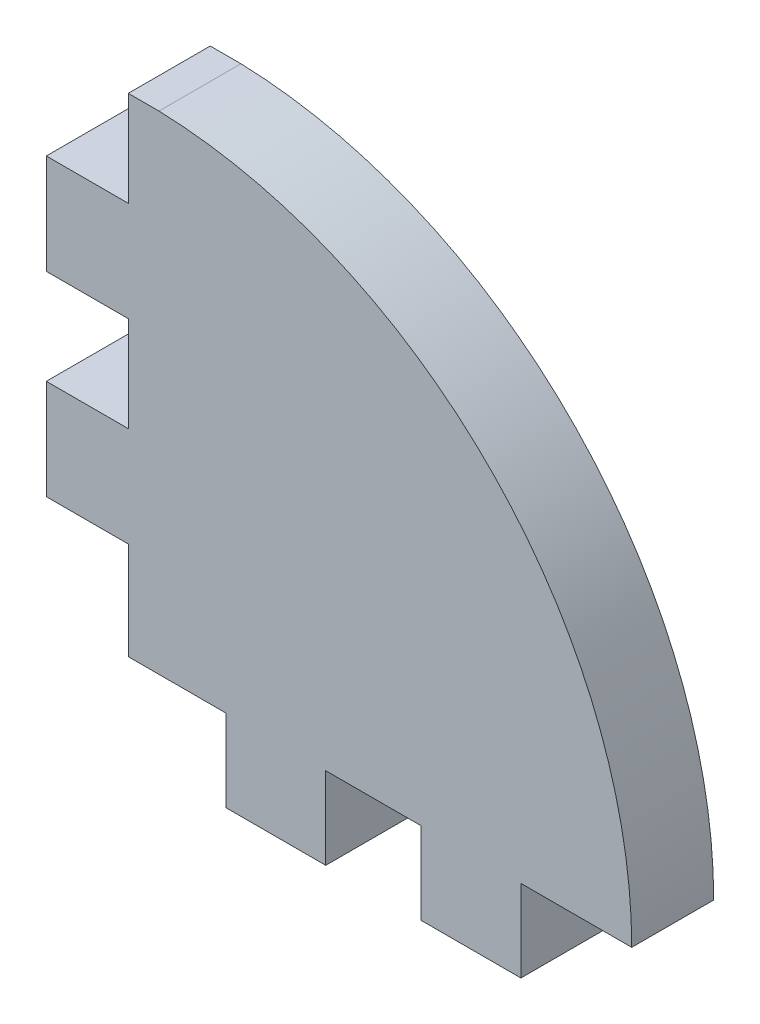
SolidWorks part; units mm, degrees
material "Oak"
ref_plane "Front Plane" through (0, 0, 0) normal (0, 0, 1) x (1, 0, 0)
ref_plane "Top Plane" through (0, 0, 0) normal (0, 1, 0) x (1, 0, 0)
ref_plane "Right Plane" through (0, 0, 0) normal (1, 0, 0) x (0, 0, -1)
sketch "Sketch1" plane through (0, 0, 0) normal (0, 0, 1) x (1, 0, 0)
  line L0 (5.334, 31.75) -> (0, 31.75) construction
  line L2 (0, -5.334) -> (38.1, -5.334)
  line L3 (0, -5.334) -> (0, 31.75)
  line L4 (0, 31.75) -> (38.1, 31.75)
  line L6 (38.1, -5.334) -> (38.1, 31.75)
  arc A0 (5.334, 31.75) -> (38.1, 0) centre (6.3342, 0) cw
extrude "Boss-Extrude1" add sketch "Sketch1" against normal blind 5.334 contours A0 L4 L3 L2 L6
sketch "Sketch2" plane through (0, 0, 0) normal (0, 0, 1) x (1, 0, 0)
  line L0 (0, -5.334) -> (38.1, -5.334) construction
  line L1 (11.684, -5.334) -> (5.4864, -5.334)
  line L2 (11.684, -5.334) -> (11.684, 0)
  line L3 (0, 31.75) -> (5.334, 31.75)
  line L4 (0, 31.75) -> (0, 25.5524)
  line L5 (0, 25.5524) -> (5.334, 25.5524)
  line L6 (5.334, 31.75) -> (5.334, 25.5524)
  line L7 (11.684, 0) -> (5.4864, 0)
  line L8 (5.4864, -5.334) -> (5.4864, 0)
  line L9 (0, 0.1524) -> (0, -5.334)
  line L10 (0, -5.334) -> (5.4864, -5.334)
  line L11 (5.334, 0.1524) -> (5.334, 0)
  line L12 (5.334, 0) -> (5.4864, 0)
  line L13 (0, 19.05) -> (0, 12.8524)
  line L14 (0, 19.05) -> (5.334, 19.05)
  line L15 (5.334, 19.05) -> (5.334, 12.8524)
  line L16 (24.384, 0) -> (18.1864, 0)
  line L17 (0, 12.8524) -> (5.334, 12.8524)
  line L18 (24.384, -5.334) -> (24.384, 0)
  line L19 (24.384, -5.334) -> (18.1864, -5.334)
  line L20 (18.1864, -5.334) -> (18.1864, 0)
  line L21 (37.084, 0) -> (30.8864, 0)
  line L22 (0, 6.35) -> (0, 0.1524)
  line L23 (0, 6.35) -> (5.334, 6.35)
  line L24 (5.334, 6.35) -> (5.334, 0.1524)
  line L25 (0, 0.1524) -> (5.334, 0.1524)
  line L26 (0, -5.334) -> (0, 31.75) construction
  line L27 (37.084, -5.334) -> (37.084, 0)
  line L28 (37.084, -5.334) -> (30.8864, -5.334)
  line L29 (30.8864, -5.334) -> (30.8864, 0)
  line L30 (37.084, 0) -> (38.1, 0)
  line L31 (38.1, 0) -> (38.1, -5.334)
  line L32 (38.1, -5.334) -> (37.084, -5.334)
  dimension "D1" = 5.334
  dimension "D2" = 6.1976
  dimension "D3" = 3
  dimension "D4" = 6.1976
  dimension "D5" = 0.1524
  dimension "D6" = 6.5024
  dimension "D7" = 3
  dimension "D8" = 6.5024
extrude "Cut-Extrude1" cut sketch "Sketch2" against normal through all
